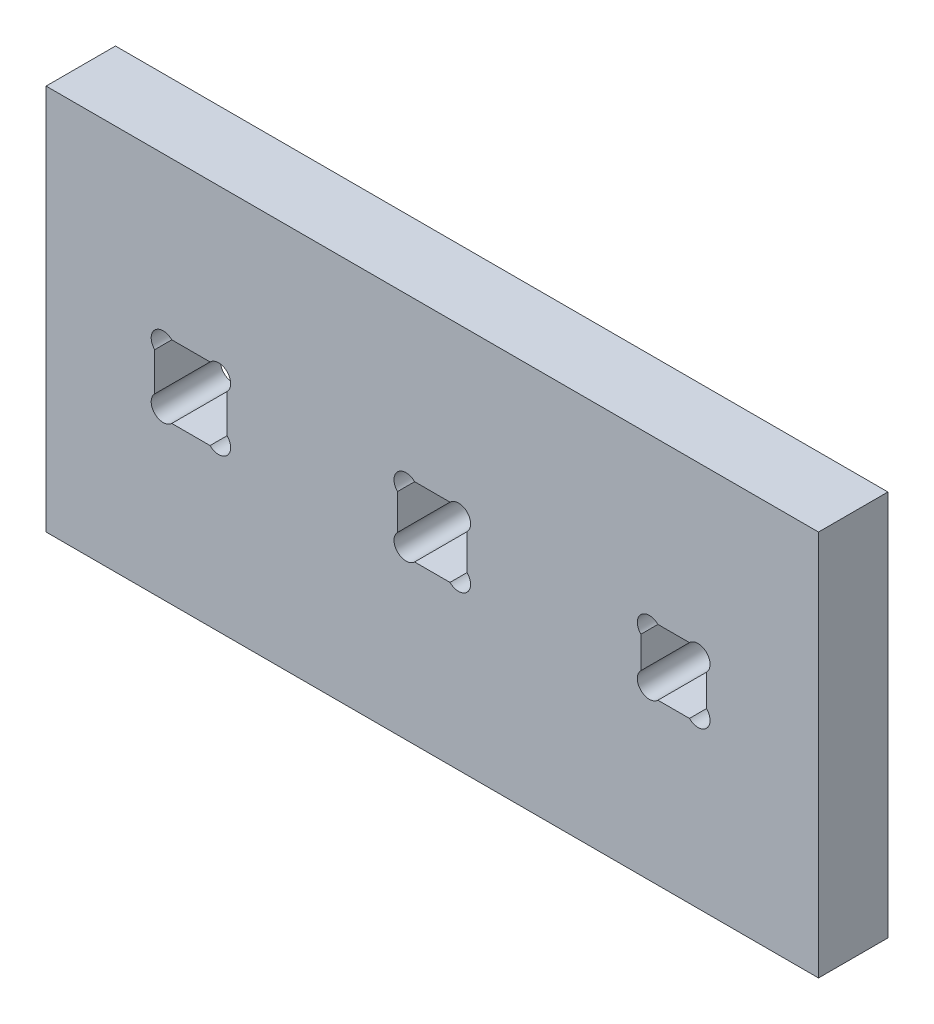
SolidWorks part; units mm, degrees
ref_plane "Front Plane" through (0, 0, 0) normal (0, 0, 1) x (1, 0, 0)
ref_plane "Top Plane" through (0, 0, 0) normal (0, 1, 0) x (1, 0, 0)
ref_plane "Right Plane" through (0, 0, 0) normal (1, 0, 0) x (0, 0, -1)
sketch "Sketch1" plane through (0, 0, 0) normal (0, 0, 1) x (1, 0, 0)
  line L0 (-9.144, -9.144) -> (9.144, -9.144)
  line L1 (-101.6, 50.8) -> (101.6, 50.8)
  line L2 (-101.6, 50.8) -> (-101.6, -50.8)
  line L3 (-101.6, -50.8) -> (101.6, -50.8)
  line L4 (101.6, 50.8) -> (101.6, -50.8)
  line L5 (-101.6, 50.8) -> (101.6, -50.8) construction
  line L6 (-101.6, -50.8) -> (101.6, 50.8) construction
  line L7 (-9.144, -9.144) -> (-9.144, 9.144)
  line L8 (-9.144, 9.144) -> (9.144, 9.144)
  line L9 (9.144, -9.144) -> (9.144, 9.144)
  line L10 (-9.144, -4.6539) -> (-4.6539, -9.144) construction
  line L11 (54.864, -8.636) -> (72.136, -8.636)
  line L12 (54.864, -8.636) -> (54.864, 8.636)
  line L13 (54.864, 8.636) -> (72.136, 8.636)
  line L14 (72.136, -8.636) -> (72.136, 8.636)
  line L15 (54.864, -4.1459) -> (59.3541, -8.636) construction
  line L16 (-73.025, -9.525) -> (-53.975, -9.525)
  line L17 (-73.025, -9.525) -> (-73.025, 9.525)
  line L18 (-73.025, 9.525) -> (-53.975, 9.525)
  line L19 (-53.975, -9.525) -> (-53.975, 9.525)
  line L20 (-73.025, -5.0349) -> (-68.5349, -9.525) construction
  arc A0 (-9.144, 4.6539) -> (-4.6539, 9.144) centre (-6.8989, 6.8989) cw
  arc A1 (4.6539, 9.144) -> (9.144, 4.6539) centre (6.8989, 6.8989) cw
  arc A2 (-9.144, -4.6539) -> (-4.6539, -9.144) centre (-6.8989, -6.8989) ccw
  arc A3 (9.144, -4.6539) -> (4.6539, -9.144) centre (6.8989, -6.8989) cw
  arc A4 (54.864, 4.1459) -> (59.3541, 8.636) centre (57.1091, 6.3909) cw
  arc A5 (67.6459, 8.636) -> (72.136, 4.1459) centre (69.8909, 6.3909) cw
  arc A6 (54.864, -4.1459) -> (59.3541, -8.636) centre (57.1091, -6.3909) ccw
  arc A7 (72.136, -4.1459) -> (67.6459, -8.636) centre (69.8909, -6.3909) cw
  arc A8 (-73.025, 5.0349) -> (-68.5349, 9.525) centre (-70.7799, 7.2799) cw
  arc A9 (-58.4651, 9.525) -> (-53.975, 5.0349) centre (-56.2201, 7.2799) cw
  arc A10 (-73.025, -5.0349) -> (-68.5349, -9.525) centre (-70.7799, -7.2799) ccw
  arc A11 (-53.975, -5.0349) -> (-58.4651, -9.525) centre (-56.2201, -7.2799) cw
  point P0 (0, 0)
  point P24 (9.144, 0)
  point P26 (0, 9.144)
  point P27 (63.5, 0)
  point P44 (72.136, 0)
  point P45 (63.5, 8.636)
  point P46 (-63.5, 0)
  point P63 (-53.975, 0)
  point P64 (-63.5, 9.525)
  dimension "D4" = 3.175
  dimension "D11" = 3.175
  dimension "D18" = 3.175
  dimension "D1" = 101.6
  dimension "8" = 203.2
  dimension "D3" = 18.288
  dimension "D5" = 6.35
  dimension "D6" = 6.35
  dimension "D7" = 6.35
  dimension "D8" = 6.35
  dimension "D9" = 45
  dimension "D10" = 17.272
  dimension "D12" = 6.35
  dimension "D13" = 6.35
  dimension "D14" = 6.35
  dimension "D15" = 6.35
  dimension "D16" = 45
  dimension "D17" = 19.05
  dimension "D19" = 6.35
  dimension "D20" = 6.35
  dimension "D21" = 6.35
  dimension "D22" = 6.35
  dimension "D23" = 45
  dimension "D24" = 63.5
  dimension "D25" = 63.5
extrude "Boss-Extrude1" add sketch "Sketch1" along normal blind 18.2562 contours L4 L1 L2 L3 A3 L0 A2 L7 A0 L8 A1 L9 A7 L11 A6 L12 A4 L13 A5 L14 A11 L16 A10 L17 A8 L18 A9 L19
